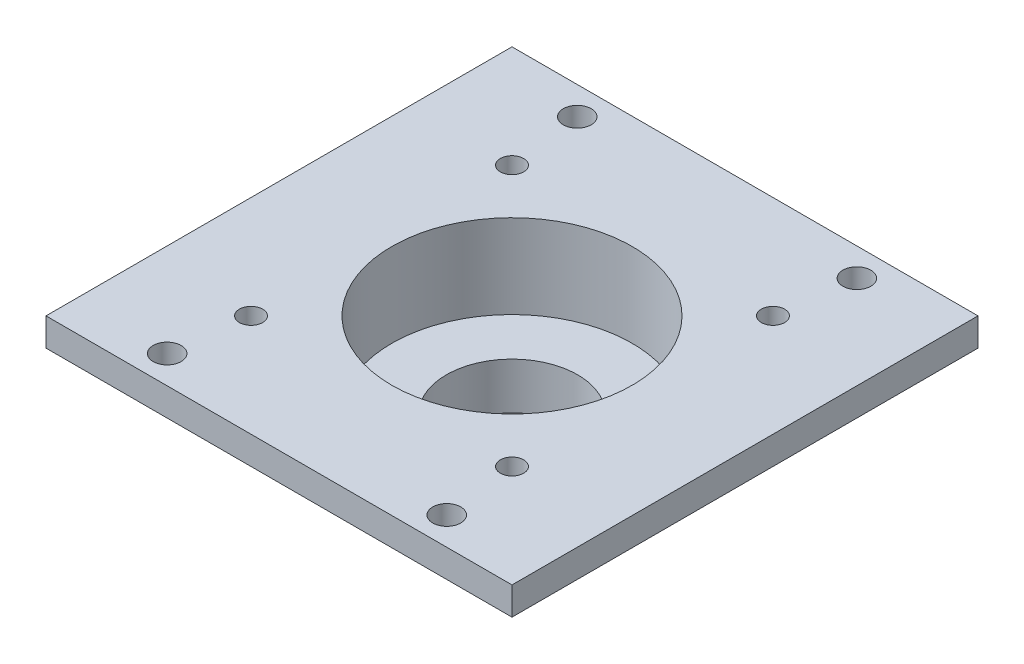
SolidWorks part; units mm, degrees
material "ABS"
ref_plane "Front Plane" through (0, 0, 0) normal (0, 0, 1) x (1, 0, 0)
ref_plane "Top Plane" through (0, 0, 0) normal (0, 1, 0) x (1, 0, 0)
ref_plane "Right Plane" through (0, 0, 0) normal (1, 0, 0) x (0, 0, -1)
sketch "Sketch2" plane through (0, 0, 0) normal (0, 0, 1) x (1, 0, 0)
  line L0 (0, 56.5286) -> (0, -39.7794) construction
  line L1 (7.05, 0) -> (7.05, 5)
  line L2 (7.05, 5) -> (12.9, 5)
  line L3 (12.9, 5) -> (12.9, 14)
  dimension "D1" = 5
  dimension "D2" = 7.05
  dimension "D3" = 9
revolve "Revolve-Thin1" add sketch "Sketch2" angle 360 about L0
sketch "Sketch3" plane through (0, 14, 0) normal (0, 1, 0) x (1, 0, 0)
  line L1 (-25, 25) -> (25, 25)
  line L2 (-25, 25) -> (-25, -25)
  line L3 (-25, -25) -> (25, -25)
  line L4 (25, 25) -> (25, -25)
  line L5 (-25, 25) -> (25, -25) construction
  line L6 (-25, -25) -> (25, 25) construction
  circle A0 centre (0, 0) radius 14.9 construction
  circle A1 centre (0, 0) radius 14.9
  point P0 (0, 0)
  dimension "D1" = 50
  dimension "D2" = 50
extrude "Boss-Extrude1" add sketch "Sketch3" against normal blind 3
sketch "Sketch4" plane through (0, 14, 0) normal (0, 1, 0) x (1, 0, 0)
  line L0 (-32.2232, 0) -> (47.8913, 0) construction
  line L3 (25, 25) -> (-25, 25) construction
  line L14 (0, 32.4348) -> (0, -29.7943) construction
  circle A0 centre (14, 14) radius 1.25
  circle A1 centre (-14, 14) radius 1.25
  circle A2 centre (-14, -14) radius 1.25
  circle A3 centre (14, -14) radius 1.25
  circle A8 centre (-15, 22) radius 1.5
  circle A9 centre (15, 22) radius 1.5
  circle A10 centre (15, -22) radius 1.5
  circle A11 centre (-15, -22) radius 1.5
  dimension "D3" = 2.5
  dimension "D6" = 3
  dimension "D4" = 3
  dimension "D1" = 14
  dimension "D2" = 14
  dimension "D5" = 15
extrude "Cut-Extrude1" cut sketch "Sketch4" against normal through all
fillet "Fillet1" radius 2 1 edges at (0, 11, 14.9)
